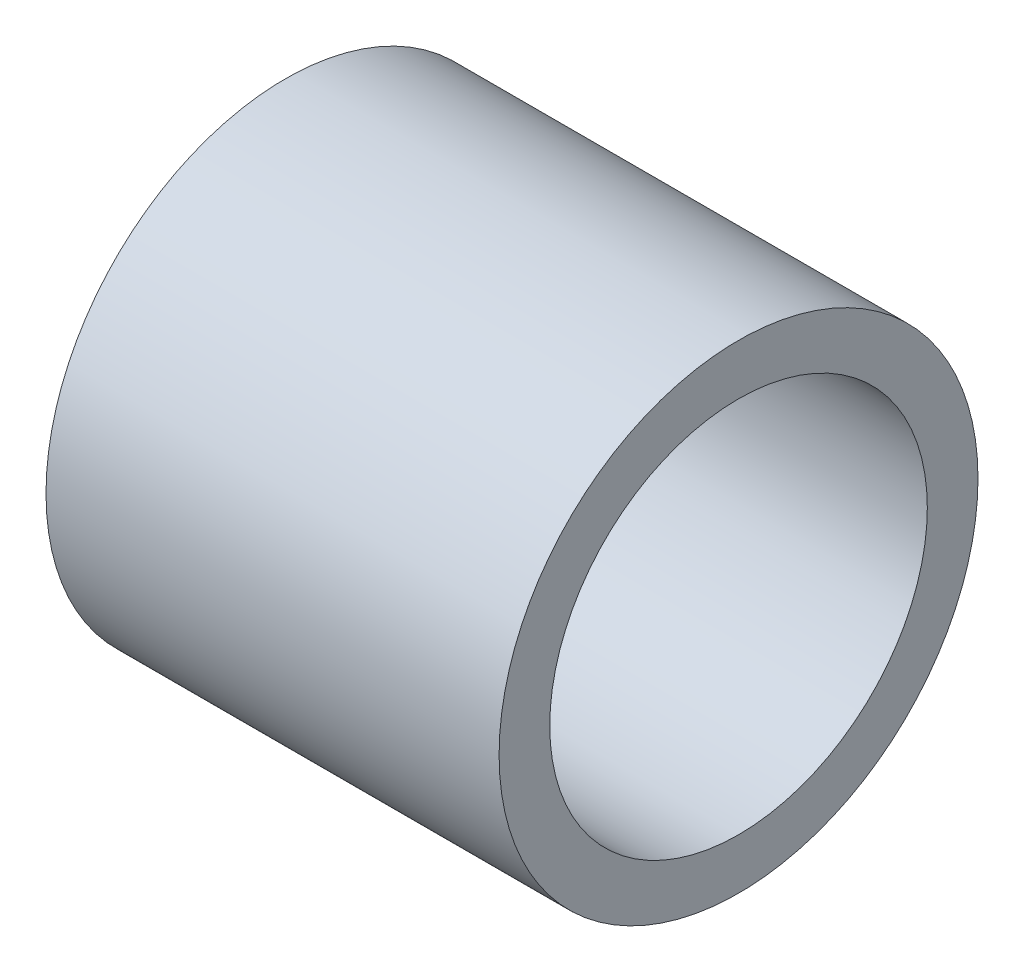
SolidWorks part; units mm, degrees
ref_plane "Front Plane" through (0, 0, 0) normal (0, 0, 1) x (1, 0, 0)
ref_plane "Top Plane" through (0, 0, 0) normal (0, 1, 0) x (1, 0, 0)
ref_plane "Right Plane" through (0, 0, 0) normal (1, 0, 0) x (0, 0, -1)
sketch "Sketch2" plane through (0, 0, 0) normal (1, 0, 0) x (0, 0, -1)
  circle A0 centre (0, 0) radius 9.525
  circle A1 centre (0, 0) radius 12.0816
extrude "Boss-Extrude1" add sketch "Sketch2" along normal blind 22.86
